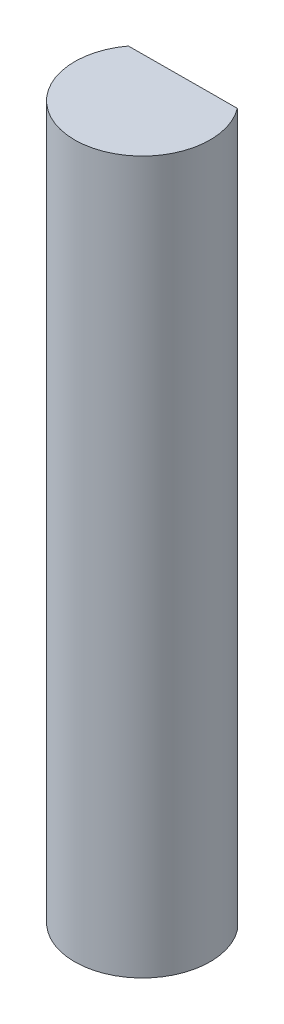
SolidWorks part; units mm, degrees
material "Plain Carbon Steel"
ref_plane "Front Plane" through (0, 0, 0) normal (0, 0, 1) x (1, 0, 0)
ref_plane "Top Plane" through (0, 0, 0) normal (0, 1, 0) x (1, 0, 0)
ref_plane "Right Plane" through (0, 0, 0) normal (1, 0, 0) x (0, 0, -1)
sketch "Sketch1" plane through (0, 0, 0) normal (0, 1, 0) x (1, 0, 0)
  circle A0 centre (0, 0) radius 3.175
  dimension "D1" = 6.35
extrude "Boss-Extrude1" add sketch "Sketch1" along normal mid plane 33.3375
sketch "Sketch2" plane through (0, 16.6687, 0) normal (0, 1, 0) x (1, 0, 0)
  line L0 (-2.5493, 1.8925) -> (2.5307, 1.9174)
  circle A0 centre (0, 0) radius 3.175 construction
  arc A1 (-2.5493, 1.8925) -> (2.5307, 1.9174) centre (0, 0) cw
  dimension "D1" = 5.08
extrude "Cut-Extrude5" cut sketch "Sketch2" against normal through all contours L0 A1
